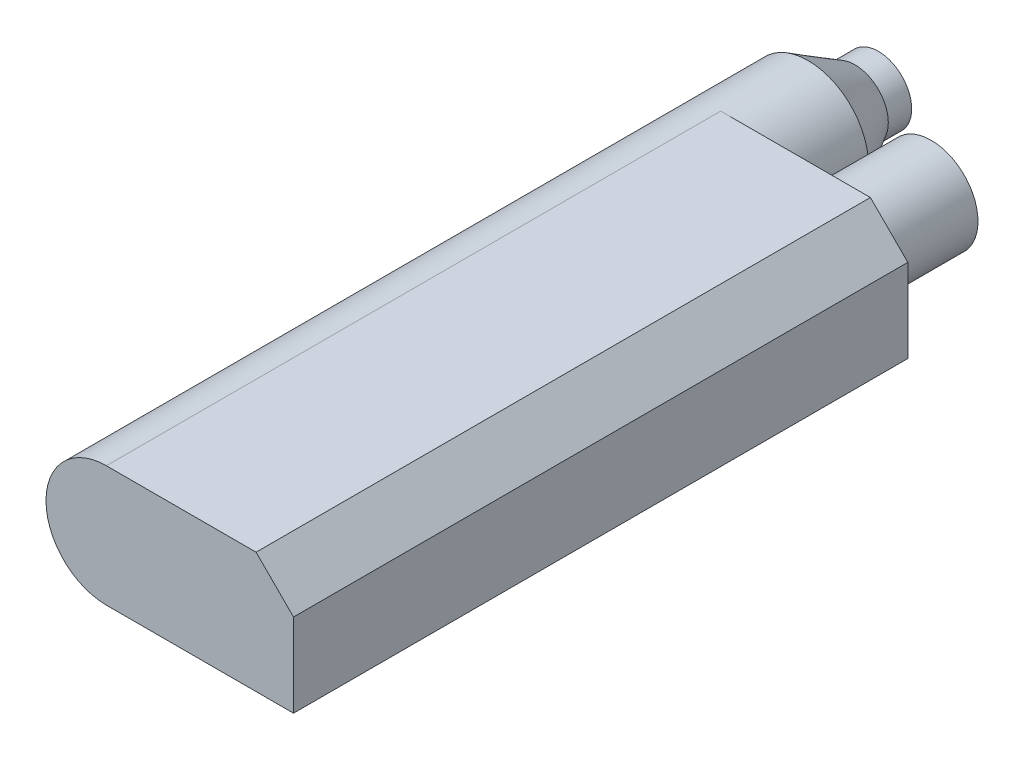
SolidWorks part; units mm, degrees
ref_plane "Front Plane" through (0, 0, 0) normal (0, 0, 1) x (1, 0, 0)
ref_plane "Top Plane" through (0, 0, 0) normal (0, 1, 0) x (1, 0, 0)
ref_plane "Right Plane" through (0, 0, 0) normal (1, 0, 0) x (0, 0, -1)
sketch "Sketch1" plane through (0, 0, 0) normal (0, 0, 1) x (1, 0, 0)
  circle A0 centre (0, 0) radius 713.105
extrude "Boss-Extrude1" add sketch "Sketch1" along normal blind 500
sketch "Sketch2" plane through (0, 0, 500) normal (0, 0, 1) x (1, 0, 0)
  circle A0 centre (0, 0) radius 713.105 construction
  circle A1 centre (0, 0) radius 713.105
extrude "Boss-Extrude3" add sketch "Sketch2" along normal blind 1000 draft 30 draft outward yes
sketch "Sketch3" plane through (0, 0, 1500) normal (0, 0, 1) x (1, 0, 0)
  circle A1 centre (0, 0) radius 1290.4553
  circle A2 centre (0, 0) radius 1290.4553
  dimension "D1" = 0
extrude "Boss-Extrude4" add sketch "Sketch3" along normal blind 15000
sketch "Sketch5" plane through (0, 0, 0) normal (1, 0, 0) x (0, 0, -1)
  line L0 (-16500, 1290.4553) -> (-16500, -1290.4553)
  line L1 (-16500, 1290.4553) -> (-3369.7125, 1290.4553)
  line L2 (-16500, -1290.4553) -> (-3369.7125, -1290.4553)
  line L3 (-3369.7125, 1290.4553) -> (-3369.7125, -1290.4553)
extrude "Boss-Extrude5" add sketch "Sketch5" along normal blind 4000
sketch "Sketch6" plane through (0, 0, 3369.7125) normal (0, 0, -1) x (-1, 0, 0)
  line L0 (1419.5008, 0) -> (-1419.5008, 0) construction
  circle A0 centre (-2500, 0) radius 1000
extrude "Boss-Extrude6" add sketch "Sketch6" along normal blind 2000
chamfer "Chamfer1" distance 800 angle 45 1 edges at (4000, 1290.4553, 9934.8563)
